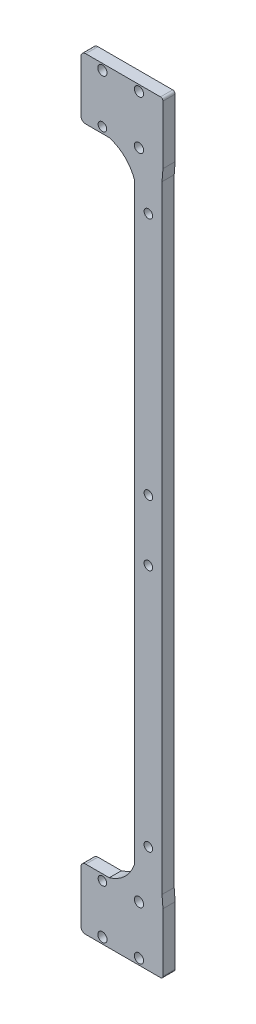
SolidWorks part; units mm, degrees
ref_plane "Front Plane" through (0, 0, 0) normal (0, 0, 1) x (1, 0, 0)
ref_plane "Top Plane" through (0, 0, 0) normal (0, 1, 0) x (1, 0, 0)
ref_plane "Right Plane" through (0, 0, 0) normal (1, 0, 0) x (0, 0, -1)
sketch "Sketch1" plane through (0, 0, 0) normal (0, 0, 1) x (1, 0, 0)
  line L1 (22.7, -12.5) -> (33.7, -12.5)
  line L5 (34.7, -11.5) -> (34.7, 12.5)
  line L8 (1, 10.5) -> (1, -10.5)
  line L9 (3, -12.5) -> (22.7, -12.5)
  line L11 (12.6768, 12.5) -> (3, 12.5)
  line L12 (34.3, 144) -> (36.3574, 144) construction
  line L13 (12.6768, 275.5) -> (3, 275.5)
  line L14 (3, 300.5) -> (22.7, 300.5)
  line L15 (1, 277.5) -> (1, 298.5)
  line L17 (23.1, 265.4476) -> (23.1, 22.5524)
  line L19 (34.3, 17.3483) -> (34.3, 270.6517)
  line L20 (34.7, 299.5) -> (34.7, 275.5)
  line L21 (22.7, 300.5) -> (33.7, 300.5)
  circle A4 centre (9.85, -10) radius 1.9
  circle A5 centre (9.85, 10) radius 1.75
  circle A6 centre (24.85, 10) radius 1.9
  circle A7 centre (24.85, -10) radius 1.9
  arc A8 (1, -10.5) -> (3, -12.5) centre (3, -10.5) ccw
  arc A11 (1, 10.5) -> (3, 12.5) centre (3, 10.5) cw
  circle A15 centre (28.7, 131.5) radius 1.75
  circle A16 centre (28.7, 156.5) radius 1.75
  circle A17 centre (28.7, 256.5) radius 1.75
  circle A18 centre (28.7, 31.5) radius 1.75
  arc A19 (1, 277.5) -> (3, 275.5) centre (3, 277.5) ccw
  arc A20 (1, 298.5) -> (3, 300.5) centre (3, 298.5) cw
  circle A21 centre (24.85, 298) radius 1.9
  circle A22 centre (24.85, 278) radius 1.9
  circle A23 centre (9.85, 278) radius 1.75
  circle A24 centre (9.85, 298) radius 1.9
  arc A25 (34.7, 299.5) -> (33.7, 300.5) centre (33.7, 299.5) ccw
  arc A26 (33.7, -12.5) -> (34.7, -11.5) centre (33.7, -11.5) ccw
  spline S0 degree 2 poles (23.1, 22.5524) (20.336, 14.9211) (12.6768, 12.5) knots 0 0 0 1 1 1
  spline S1 degree 2 poles (34.3, 17.3483) (34.5298, 14.9266) (34.7, 12.5) knots 0 0 0 1 1 1
  spline S2 degree 2 poles (34.3, 270.6517) (34.5298, 273.0734) (34.7, 275.5) knots 0 0 0 1 1 1
  spline S3 degree 2 poles (23.1, 265.4476) (20.336, 273.0789) (12.6768, 275.5) knots 0 0 0 1 1 1
  point P27 (34.5532, 14.4538)
  point P57 (34.7, 300.5)
  point P60 (34.7, -12.5)
  dimension "D1" = 1
extrude "Boss-Extrude1" add sketch "Sketch1" along normal blind 5
